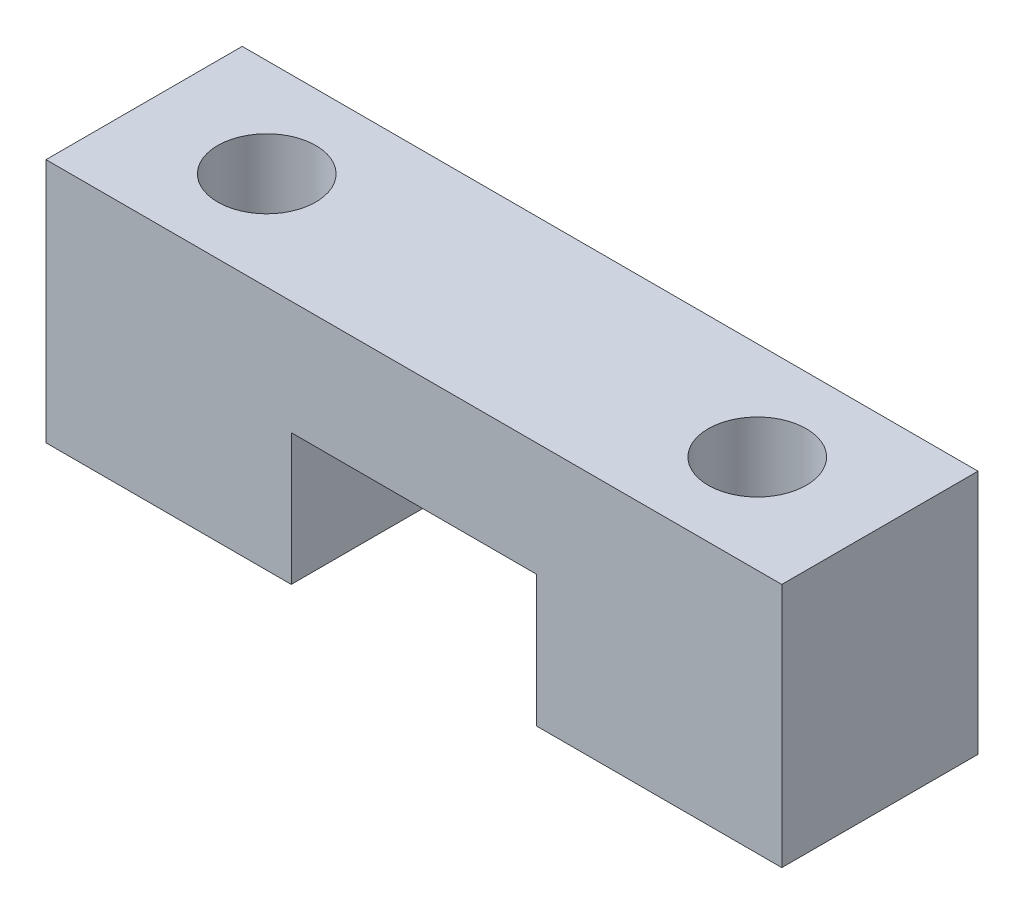
SolidWorks part; units mm, degrees
material "PET"
ref_plane "Front Plane" through (0, 0, 0) normal (0, 0, 1) x (1, 0, 0)
ref_plane "Top Plane" through (0, 0, 0) normal (0, 1, 0) x (1, 0, 0)
ref_plane "Right Plane" through (0, 0, 0) normal (1, 0, 0) x (0, 0, -1)
sketch "Sketch1" plane through (0, 0, 0) normal (0, 0, 1) x (1, 0, 0)
  line L0 (0, 0) -> (6.35, 0)
  line L1 (6.35, 0) -> (6.35, 3.4036)
  line L2 (6.35, 3.4036) -> (12.7, 3.4036)
  line L3 (12.7, 3.4036) -> (12.7, 0)
  line L4 (12.7, 0) -> (19.05, 0)
  line L5 (19.05, 0) -> (19.05, 6.35)
  line L6 (19.05, 6.35) -> (0, 6.35)
  line L7 (0, 6.35) -> (0, 0)
  dimension "D1" = 6.35
  dimension "D2" = 19.05
  dimension "D3" = 3.4036
  dimension "D4" = 6.35
extrude "Boss-Extrude1" add sketch "Sketch1" along normal blind 5.08
sketch "Sketch2" plane through (0, 6.35, 0) normal (0, 1, 0) x (1, 0, 0)
  line L0 (0, -2.54) -> (3.175, -2.54)
  line L1 (0, -5.08) -> (0, 0) construction
  line L2 (3.175, -2.54) -> (15.875, -2.54)
  line L3 (15.875, -2.54) -> (19.05, -2.54)
  line L4 (19.05, -5.08) -> (19.05, 0) construction
  circle A0 centre (3.175, -2.54) radius 1.27
  circle A1 centre (15.875, -2.54) radius 1.27
  dimension "D2" = 2.54
  dimension "D3" = 2.54
  dimension "D1" = 12.7
extrude "Cut-Extrude1" cut sketch "Sketch2" against normal through all contours A0 | A1
